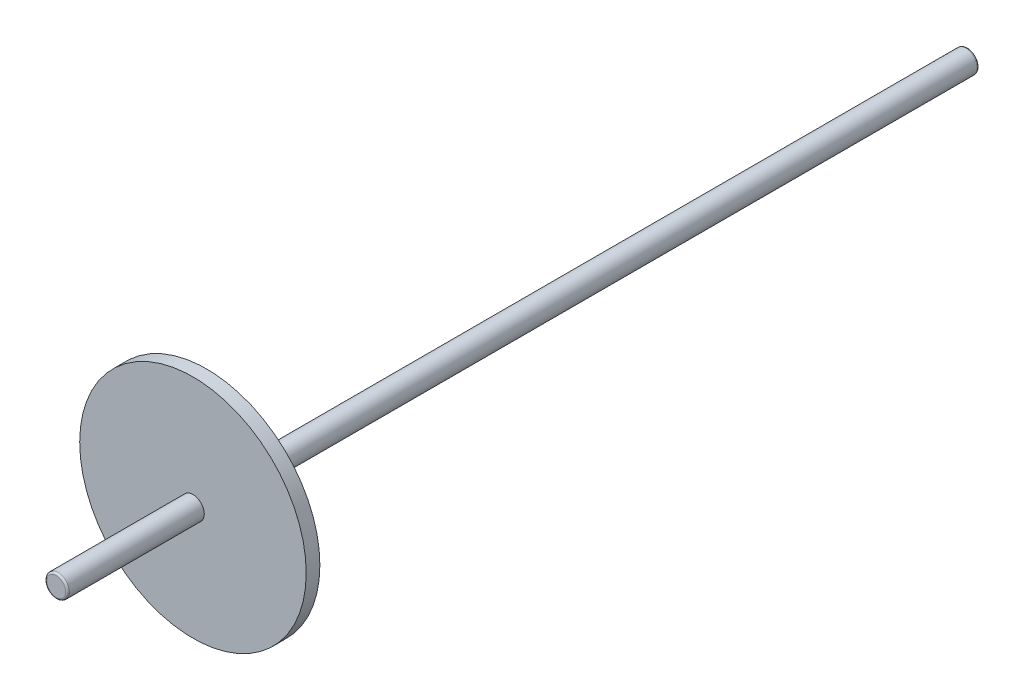
SolidWorks part; units mm, degrees
ref_plane "Plano frontal" through (0, 0, 0) normal (0, 0, 1) x (1, 0, 0)
ref_plane "Plano superior" through (0, 0, 0) normal (0, 1, 0) x (1, 0, 0)
ref_plane "Plano direito" through (0, 0, 0) normal (1, 0, 0) x (0, 0, -1)
sketch "Esboço1" plane through (0, 0, 0) normal (0, 0, 1) x (1, 0, 0)
  circle A0 centre (0, 0) radius 12.425
  circle A1 centre (0, 0) radius 1.2415
  dimension "D1" = 24.85
  dimension "D2" = 2.483
extrude "Ressalto-extrusão1" add sketch "Esboço1" along normal blind 1.5
sketch "Esboço2" plane through (0, 0, 0) normal (0, 0, 1) x (1, 0, 0)
  circle A0 centre (0, 0) radius 1.2415
  circle A1 centre (0, 0) radius 2.2
  dimension "D1" = 4.4
extrude "Ressalto-extrusão2" add sketch "Esboço2" against normal blind 1
ref_plane "Plano1" through (0, 0, 16.5) normal (0, 0, 1) x (1, 0, 0)
sketch "Esboço3" plane through (0, 0, 16.5) normal (0, 0, 1) x (1, 0, 0)
  circle A0 centre (0, 0) radius 1.2415
extrude "Ressalto-extrusão3" add sketch "Esboço3" against normal blind 100
fillet "Filete1" radius 0.2 2 edges at (1.2415, 0, -83.5) (1.2415, 0, 16.5)
